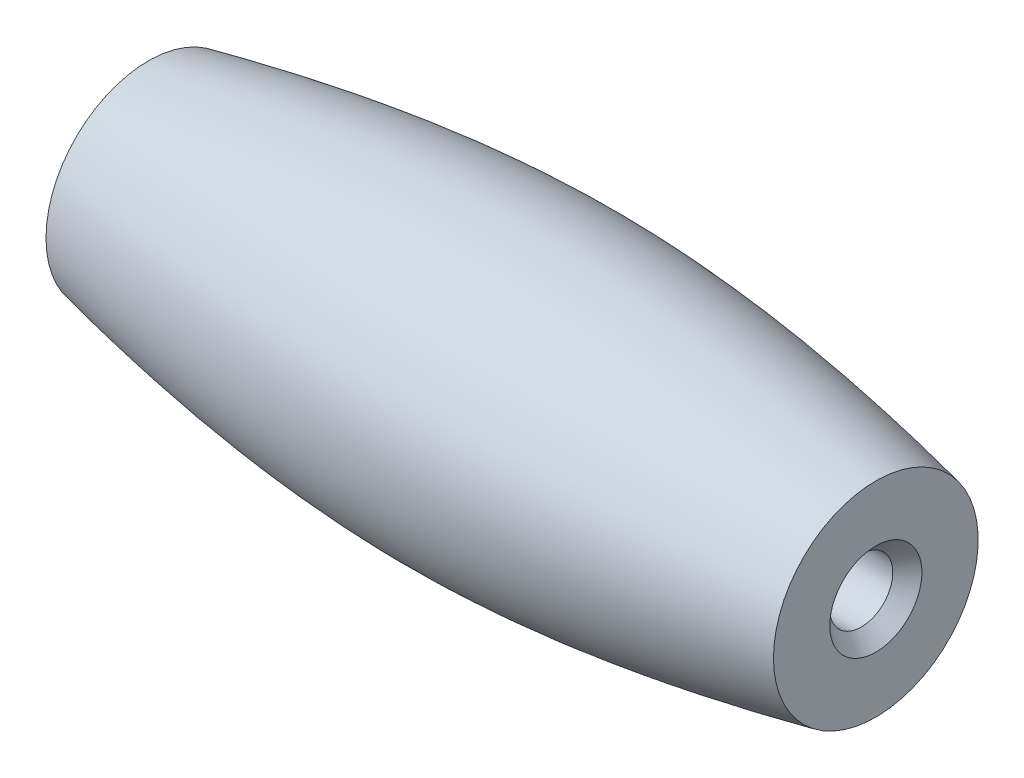
SolidWorks part; units mm, degrees
material "天然橡胶"
ref_plane "前视基准面" through (0, 0, 0) normal (0, 0, 1) x (1, 0, 0)
ref_plane "上视基准面" through (0, 0, 0) normal (0, 1, 0) x (1, 0, 0)
ref_plane "右视基准面" through (0, 0, 0) normal (1, 0, 0) x (0, 0, -1)
sketch "草图1" plane through (0, 0, 0) normal (0, 1, 0) x (1, 0, 0)
  line L0 (4.2023, -13.1806) -> (4.2023, -8.9601)
  line L1 (4.2023, -13.1806) -> (34.2023, -13.1806)
  line L2 (34.2023, -13.1806) -> (34.2023, -8.9601)
  line L6 (35.0023, -13.9806) -> (35.0023, -8.3123)
  line L7 (3.4023, -13.9806) -> (35.0023, -13.9806)
  line L8 (3.4023, -13.9806) -> (3.4023, -8.3123)
  line L9 (4.2023, -13.1806) -> (3.4023, -13.1806)
  line L10 (34.2023, -13.1806) -> (35.0023, -13.1806)
  line L11 (34.2023, -8.9601) -> (34.2023, -8.1423)
  line L12 (4.2023, -8.9601) -> (4.2023, -8.1423)
  spline S0 degree 3 poles (4.2023, -8.9601) (9.2817, -7.8804) (19.1758, -6.4752) (29.1757, -7.8917) (34.2023, -8.9601) knots 0 0 0 0 0.5 1 1 1 1
  spline S1 degree 3 poles (3.4023, -8.3123) (3.6019, -8.2698) (3.9339, -8.199) (5.2667, -7.9174) (7.7187, -7.4361) (12.6461, -6.67) (19.1997, -6.1851) (25.7848, -6.6778) (30.7169, -7.4433) (33.1507, -7.9202) (34.4709, -8.199) (34.802, -8.2697) (35.0023, -8.3123) knots -0.020792 -0.020792 -0.020792 -0.020792 -0.001131 0.011976 0.109434 0.239659 0.50011 0.76056 0.890786 0.987901 1.001145 1.021011 1.021011 1.021011 1.021011
revolve "旋转1" add sketch "草图1" angle 360 about L1
sketch "草图2" plane through (34.2023, 0, 0) normal (1, 0, 0) x (0, 0, -1)
  circle A0 centre (-13.1806, 0) radius 1.3
  dimension "D1" = 2.6
extrude "切除-拉伸1" cut sketch "草图2" against normal through all
chamfer "倒角1" distance 0.6 angle 45 2 edges at (34.2023, 0, 11.8806) (4.2023, 0, 11.8806)
